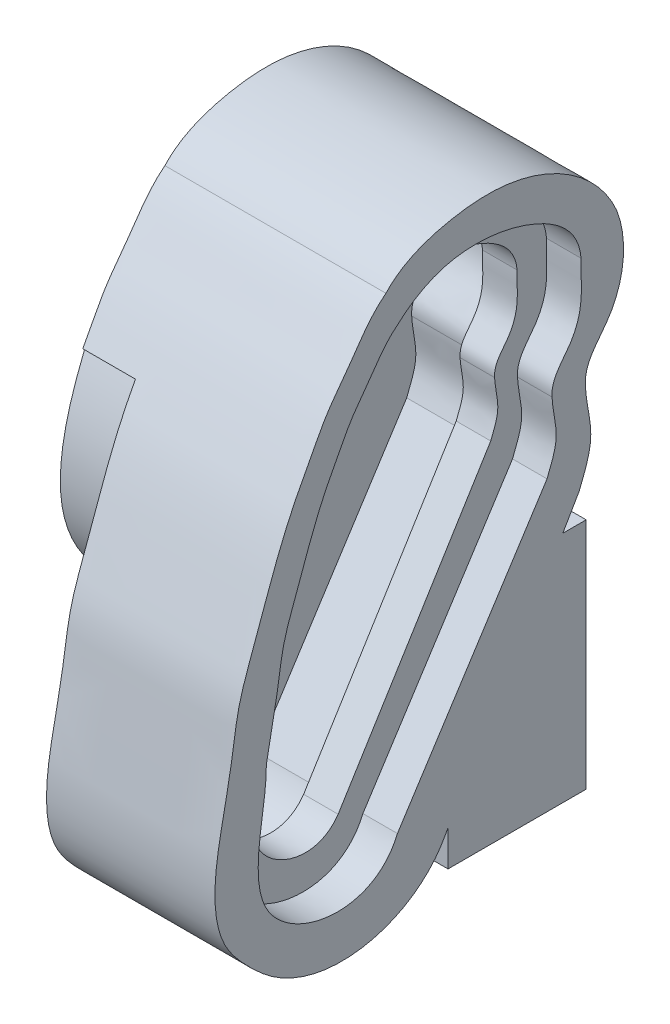
SolidWorks part; units mm, degrees
ref_plane "Front Plane" through (0, 0, 0) normal (0, 0, 1) x (1, 0, 0)
ref_plane "Top Plane" through (0, 0, 0) normal (0, 1, 0) x (1, 0, 0)
ref_plane "Right Plane" through (0, 0, 0) normal (1, 0, 0) x (0, 0, -1)
sketch "Sketch1" plane through (0, 0, 0) normal (1, 0, 0) x (0, 0, -1)
  line L0 (-4.732, 33.782) -> (-20, 5.4187)
  line L1 (0, 0) -> (-20, 0)
  line L2 (0, 0) -> (0, 33.782)
  line L3 (0, 33.782) -> (-4.732, 33.782)
  line L4 (-20, 0) -> (-20, 5.4187)
  dimension "D1" = 33.782
extrude "Boss-Extrude1" add sketch "Sketch1" along normal blind 32.004
sketch "Sketch2" plane through (0, 0, 20) normal (0, 0, 1) x (1, 0, 0)
  line L0 (0, 5.4187) -> (0, 0) construction
  line L11 (32.004, 0) -> (0, 0) construction
  line L12 (10.16, 0) -> (0, 0)
  line L13 (10.16, 0) -> (10.16, 33.782)
  line L14 (10.16, 33.782) -> (0, 33.782)
  line L15 (0, 0) -> (0, 33.782)
  point P0 (0, 0)
  point P4 (0, 0)
  dimension "D1" = 10.16
extrude "Cut-Extrude1" cut sketch "Sketch2" against normal up to surface (20 mm away) up to face at (16.002, 16.891, 0)
sketch "Sketch3" plane through (32.004, 0, 0) normal (1, 0, 0) x (0, 0, -1)
  line L2 (-51.7111, 23.6049) -> (31.7012, 78.7627) construction
  line L3 (120.139, 43.2961) -> (447.3438, 733.6604) construction
  line L4 (-21.5333, 2.119) -> (-17.5701, 10.1994) construction
  line L5 (-53.4765, 5.1685) -> (-14.8397, 86.4531) construction
  line L6 (-1.0419, 37.8196) -> (-20.4257, 4.4111)
  spline S0 degree 3 poles (-28.9909, 76.6796) (-31.2329, 74.9637) (-33.733, 70.824) (-37.4975, 66.1466) (-39.9033, 61.43) (-42.2272, 57.2375) (-44.2641, 52.5486) (-46.0532, 47.8446) (-47.9924, 42.1579) (-50.3842, 36.19) (-51.2203, 29.367) (-52.6552, 22.1898) (-54.2137, 14.4316) (-53.1583, 7.0263) (-49.149, 2.3159) (-44.7992, -1.6761) (-34.1139, -5.7604) (-23.8212, -1.9175) (-20.4257, 4.4111) knots 0 0 0 0 0.072421 0.125935 0.156715 0.210822 0.251532 0.290505 0.342632 0.409161 0.457775 0.521963 0.600976 0.665387 0.707932 0.760163 0.818987 1 1 1 1
  spline S1 degree 3 poles (-28.9909, 76.6796) (-26.7392, 79.1129) (-21.0307, 81.2707) (-12.5381, 82.1155) (-2.9216, 79.6403) (2.6419, 74.5208) (4.4436, 70.3285) knots 0 0 0 0 0.249519 0.45668 0.650575 1 1 1 1
  spline S2 degree 3 poles (4.4436, 70.3285) (5.4854, 67.5753) (5.8287, 62.9189) (3.0362, 56.3074) (-0.3459, 53.5647) (-0.1033, 50.585) knots 0 0 0 0 0.417925 0.630287 1 1 1 1
  spline S3 degree 3 poles (-0.1033, 50.585) (-0.03, 48.2784) (1.5103, 43.8402) (-0.3194, 39.6098) (-1.0419, 37.8196) knots 0 0 0 0 0.545479 1 1 1 1
  dimension "D1" = 100
  dimension "D2" = 9
  dimension "D3" = 90
extrude "Boss-Extrude2" add sketch "Sketch3" against normal blind 32.004
sketch "Sketch12" plane through (0, 0, 0) normal (-1, 0, 0) x (0, 0, 1)
  line L0 (-11.9892, 69.551) -> (51.4002, 22.8416) construction
  line L1 (0, 26.8622) -> (30.459, 27.7535)
  line L2 (73.088, 4.289) -> (73.088, -7.7362)
  line L3 (73.088, -7.7362) -> (0, -7.7362)
  line L4 (0, -7.7362) -> (0, 26.8622)
  line L5 (40.5405, 59.6654) -> (76.5732, 59.6654)
  line L6 (76.5732, 59.6654) -> (73.088, 4.289)
  spline S0 degree 3 poles (40.5405, 59.6654) (42.9098, 53.84) (47.2039, 40.1584) (37.5508, 28.1814) (30.459, 27.7535) knots 0 0 0 0 0.50313 1 1 1 1
  point P6 (0, 0)
  point P8 (0, 0)
  point P10 (0, 0)
  point P14 (0, 0)
  point P15 (0, 0)
  dimension "D1" = 78.74
extrude "Cut-Extrude12" cut sketch "Sketch12" against normal blind 7.62
sketch "Sketch5" plane through (32.004, 0, 0) normal (1, 0, 0) x (0, 0, -1)
  line L0 (-47.0595, 27.2029) -> (16.1226, 68.8839) construction
  line L5 (113.5957, 42.3234) -> (116.6006, 48.6456) construction
  line L6 (-49.7766, 13.0905) -> (-19.7144, 76.3065) construction
  line L7 (-48.693, 17.606) -> (-18.64, 80.8263) construction
  line L8 (-54.3559, 15.187) -> (-24.3218, 78.4164) construction
  line L9 (-5.6648, 41.7453) -> (-27.3253, 8.1086)
  spline S0 degree 3 poles (-46.312, 26.195) (-46.1255, 21.1277) (-52.7093, 3.6007) (-30.7847, -0.1783) (-27.3253, 8.1086) knots 0 0 0 0 0.459345 1 1 1 1
  spline S1 degree 3 poles (-27.3253, 71.8618) (-29.0629, 70.5321) (-31.0004, 67.3238) (-33.9179, 63.6988) (-35.7825, 60.0433) (-37.5834, 56.7946) (-39.1622, 53.1593) (-40.5478, 49.5191) (-42.0562, 45.0821) (-43.8851, 40.5914) (-44.6124, 34.872) (-45.1323, 32.3973) (-46.0772, 27.4945) (-46.312, 26.195) knots 0 0 0 0 0.068256 0.118692 0.147702 0.198697 0.237065 0.273797 0.322925 0.385628 0.431446 0.491942 0.516683 0.516683 0.516683 0.516683
  spline S2 degree 3 poles (-27.3253, 71.8618) (-25.453, 73.6106) (-21.3547, 76.0812) (-14.5059, 76.5787) (-6.6875, 74.9245) (-1.087, 71.2296) (-0.7365, 66.9398) knots 0 0 0 0 0.24281 0.435179 0.631945 1 1 1 1
  spline S3 degree 3 poles (-0.7365, 66.9398) (-0.8206, 64.7253) (-0.3001, 61.1782) (-2.5251, 56.071) (-5.1165, 53.9489) (-4.9374, 51.6385) knots 0 0 0 0 0.415081 0.62848 1 1 1 1
  spline S4 degree 3 poles (-4.9374, 51.6385) (-4.8806, 49.8509) (-3.6869, 46.4113) (-5.1049, 43.1327) (-5.6648, 41.7453) knots 0 0 0 0 0.545479 1 1 1 1
  point P8 (-8.4842, 53.8533)
  point P9 (-35.2619, 14.0171)
  point P10 (-45.3868, 8.5712)
  point P11 (-13.0407, 69.9276)
  point P14 (-52.8626, 12.878)
  point P15 (-55.6751, 22.3288)
  point P18 (-54.4788, 13.835)
  point P30 (-34.3877, 54.6571)
  dimension "D1" = 7
  dimension "D2" = 70
  dimension "D3" = 70
  dimension "D4" = 70
extrude "Cut-Extrude2" cut sketch "Sketch5" against normal blind 20.32
sketch "Sketch8" plane through (32.004, 0, 0) normal (1, 0, 0) x (0, 0, -1)
  line L0 (-42.5367, 19.4528) -> (16.3785, 58.3765) construction
  line L1 (-49.4198, 20.3763) -> (22.2283, 67.6744) construction
  line L2 (-41.588, 26.4661) -> (14.1677, 63.2604) construction
  line L3 (-43.2869, 29.7532) -> (12.4492, 66.5769) construction
  line L4 (-42.0219, 30.9666) -> (9.4868, 64.9733) construction
  line L10 (-20.4592, 78.8981) -> (-27.1309, 74.0117)
  line L13 (-27.1309, 74.0117) -> (-33.6418, 67.3835)
  line L14 (-8.8168, 45.5705) -> (-30.9055, 9.8158)
  line L15 (-33.6418, 67.3835) -> (-40.719, 56.9339)
  line L16 (-40.719, 56.9339) -> (-45.204, 44.1531)
  line L17 (-45.204, 44.1531) -> (-47.4844, 31.3371)
  line L18 (-47.4844, 31.3371) -> (-50.9048, 17.8181)
  line L19 (-50.9048, 17.8181) -> (-49.1946, 6.2536)
  line L20 (-49.1946, 6.2536) -> (-42.2883, 1.5762)
  line L21 (-42.2883, 1.5762) -> (-30.9055, -1.3038)
  line L22 (-30.9055, -1.3038) -> (-7.42, 33.3732)
  line L23 (-7.42, 33.3732) -> (-2.2037, 42.2805)
  line L24 (-2.2037, 42.2805) -> (-2.2037, 50.5598)
  line L25 (-2.2037, 50.5598) -> (-0.4761, 57.388)
  line L26 (-0.4761, 57.388) -> (1.4742, 65.0962)
  line L27 (1.4742, 65.0962) -> (-0.4761, 74.0117)
  line L28 (-0.4761, 74.0117) -> (-8.8168, 78.8961)
  line L29 (-8.8168, 78.8961) -> (-20.4592, 78.8981)
  spline S0 degree 3 poles (-40.719, 33.3732) (-41.7147, 26.097) (-48.9983, 9.2881) (-33.4977, 6.1149) (-30.9055, 9.8158) knots 0 0 0 0 0.686483 1 1 1 1
  spline S1 degree 3 poles (-25.6036, 68.9108) (-26.9503, 67.8802) (-28.4519, 65.3939) (-30.7129, 62.5844) (-32.1579, 59.7517) (-33.5537, 57.2319) (-34.7773, 54.421) (-35.8511, 51.5761) (-37.0202, 48.2672) (-38.4368, 44.2027) (-39.0031, 41.6448) (-38.8081, 42.4064) (-40.537, 34.3803) (-40.719, 33.3732) knots 0 0 0 0 0.068256 0.118692 0.147702 0.198697 0.237065 0.273797 0.322925 0.385628 0.431446 0.491942 0.516683 0.516683 0.516683 0.516683
  spline S2 degree 3 poles (-25.6036, 68.9108) (-24.1526, 70.2661) (-20.9764, 72.1808) (-15.6686, 72.5664) (-9.6093, 71.2844) (-5.2689, 68.4208) (-4.9973, 65.0962) knots 0 0 0 0 0.24281 0.435179 0.631945 1 1 1 1
  spline S3 degree 3 poles (-4.9973, 65.0962) (-5.0625, 63.3799) (-4.6591, 60.631) (-6.3835, 56.6729) (-8.3918, 55.0282) (-8.253, 53.2377) knots 0 0 0 0 0.415081 0.62848 1 1 1 1
  spline S4 degree 3 poles (-8.253, 53.2377) (-8.209, 51.8523) (-7.2839, 49.1866) (-8.3828, 46.6457) (-8.8168, 45.5705) knots 0 0 0 0 0.545479 1 1 1 1
  point P10 (-11.3213, 47.4011)
  point P11 (-15.8778, 63.4753)
  point P20 (-37.2248, 48.2049)
extrude "Boss-Extrude3" add sketch "Sketch8" against normal blind 5 from offset 5
